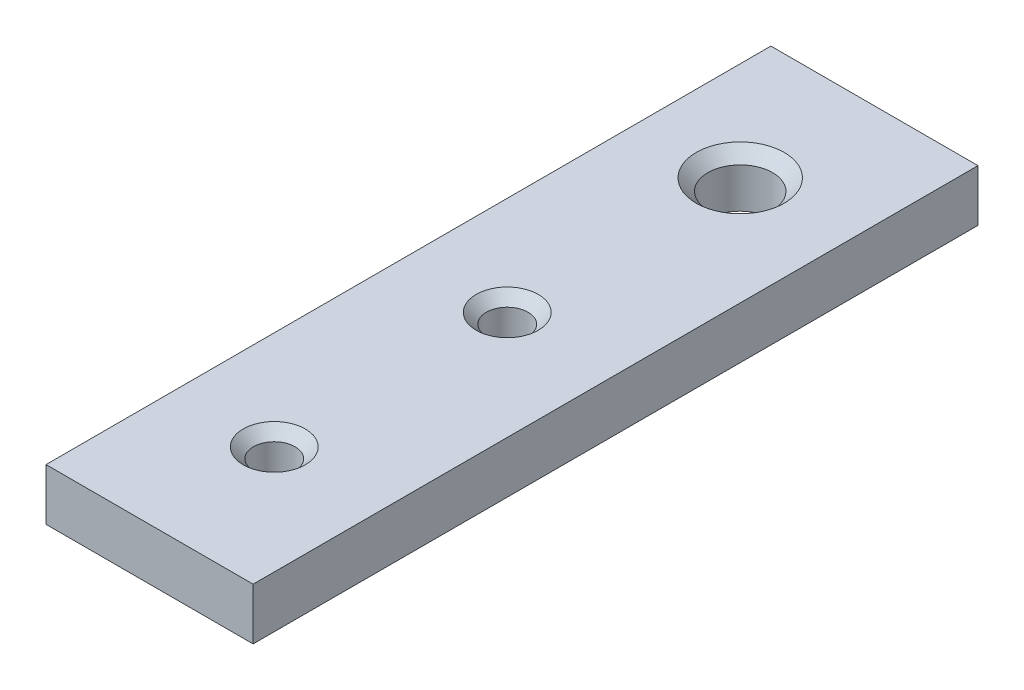
SolidWorks part; units mm, degrees
material "6061 Alloy"
ref_plane "Front Plane" through (0, 0, 0) normal (0, 0, 1) x (1, 0, 0)
ref_plane "Top Plane" through (0, 0, 0) normal (0, 1, 0) x (1, 0, 0)
ref_plane "Right Plane" through (0, 0, 0) normal (1, 0, 0) x (0, 0, -1)
sketch "Sketch1" plane through (0, 0, 0) normal (0, 1, 0) x (1, 0, 0)
  line L1 (0, 0) -> (-25.4, 0)
  line L2 (0, 0) -> (0, 88.9)
  line L3 (0, 88.9) -> (-25.4, 88.9)
  line L4 (-25.4, 0) -> (-25.4, 88.9)
  dimension "D1" = 88.9
  dimension "D2" = 25.4
extrude "Boss-Extrude1" add sketch "Sketch1" along normal blind 6.35
hole_wizard "1/4-20 Tapped Hole1" positions "Sketch2" profile "Sketch3" tap size "1/4-20" standard "ANSI Inch" end condition through all
sketch "Sketch2" plane through (0, 6.35, 0) normal (0, 1, 0) x (1, 0, 0)
  line L0 (-25.4, 0) -> (0, 0) construction
  point P0 (-13.2844, 15.875)
  point P2 (-13.2844, 44.45)
  dimension "D1" = 15.875
  dimension "D3" = 44.45
sketch "Sketch3" plane through (-13.2844, 6.35, -15.875) normal (1, 0, 0) x (0, 0, 1)
  line L0 (0, 0) -> (0, 6.35)
  line L1 (0, 6.35) -> (2.5527, 6.35)
  line L2 (2.5527, 6.35) -> (2.5527, 1.2573)
  line L3 (2.5527, 1.2573) -> (3.81, 0)
  line L5 (3.81, 0) -> (0, 0)
  line L6 (-2.5527, 1.2573) -> (-3.81, 0) construction
  line L11 (0, -6.35) -> (0, 107.95) construction
  dimension "Thru Tap Drill Dia." = 5.1054
  dimension "Thru Tap Drill Depth" = 6.35
  dimension "Near C'Sink Dia." = 7.62
  dimension "Near C'Sink Angle" = 90
cosmetic thread "Hole Thread2"
cosmetic thread "Hole Thread3"
hole_wizard "3/8-16 Tapped Hole1" positions "Sketch4" profile "Sketch5" tap size "3/8-16" standard "ANSI Inch" end condition through all
sketch "Sketch4" plane through (0, 6.35, 0) normal (0, 1, 0) x (1, 0, 0)
  line L0 (0, 88.9) -> (-25.4, 88.9) construction
  point P0 (-13.2844, 73.025)
  dimension "D1" = 15.875
sketch "Sketch5" plane through (-13.2844, 6.35, -73.025) normal (1, 0, 0) x (0, 0, 1)
  line L0 (0, 0) -> (0, 6.35)
  line L1 (0, 6.35) -> (3.9687, 6.35)
  line L2 (3.9687, 6.35) -> (3.9687, 1.4287)
  line L3 (3.9687, 1.4287) -> (5.3975, 0)
  line L5 (5.3975, 0) -> (0, 0)
  line L6 (-3.9687, 1.4287) -> (-5.3975, 0) construction
  line L11 (0, -6.35) -> (0, 107.95) construction
  dimension "Thru Tap Drill Dia." = 7.9375
  dimension "Thru Tap Drill Depth" = 6.35
  dimension "Near C'Sink Dia." = 10.795
  dimension "Near C'Sink Angle" = 90
cosmetic thread "Hole Thread4"
